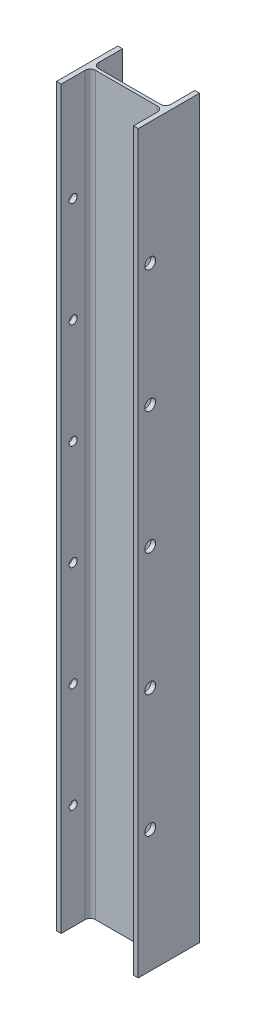
SolidWorks part; units mm, degrees
material "Plain Carbon Steel"
ref_plane "Front Plane" through (0, 0, 0) normal (0, 0, 1) x (1, 0, 0)
ref_plane "Top Plane" through (0, 0, 0) normal (0, 1, 0) x (1, 0, 0)
ref_plane "Right Plane" through (0, 0, 0) normal (1, 0, 0) x (0, 0, -1)
sketch3d "3DSketch1"
  line L1 (3.175, -457.2, -609.6) -> (3.175, -457.2, 0) construction
  line L2 (-3.175, -457.2, 0) -> (3.175, -457.2, 0) construction
  line L3 (53.975, -457.2, -38.1) -> (53.975, 457.2, -38.1)
  point P0 (53.975, -457.2, -38.1)
  point P6 (53.975, 457.2, -38.1)
  dimension "D1" = 50.8
  dimension "D2" = 38.1
other "Al i beam AL I BEAM 4X2.31(4)"
ref_plane "Plane1" through (53.975, -457.2, -38.1) normal (0, 1, 0) x (0, 0, -1)
sketch "Sketch11" plane through (53.975, -457.2, -38.1) normal (0, 1, 0) x (0, 0, -1)
  line L0 (-38.1, -50.8) -> (-38.1, -44.958)
  line L1 (-38.1, -44.958) -> (-8.255, -44.958)
  line L2 (-1.905, -38.608) -> (-1.905, 38.608)
  line L3 (-8.255, 44.958) -> (-38.1, 44.958)
  line L4 (-38.1, 44.958) -> (-38.1, 50.8)
  line L5 (-38.1, 50.8) -> (38.1, 50.8)
  line L6 (38.1, 50.8) -> (38.1, 44.958)
  line L7 (38.1, 44.958) -> (8.255, 44.958)
  line L8 (1.905, 38.608) -> (1.905, -38.608)
  line L9 (8.255, -44.958) -> (38.1, -44.958)
  line L10 (38.1, -44.958) -> (38.1, -50.8)
  line L11 (38.1, -50.8) -> (-38.1, -50.8)
  line L12 (1.905, 0) -> (-1.905, 0) construction
  arc A0 (-8.255, -44.958) -> (-1.905, -38.608) centre (-8.255, -38.608) ccw
  arc A1 (-1.905, 38.608) -> (-8.255, 44.958) centre (-8.255, 38.608) ccw
  arc A2 (8.255, 44.958) -> (1.905, 38.608) centre (8.255, 38.608) ccw
  arc A3 (1.905, -38.608) -> (8.255, -44.958) centre (8.255, -38.608) ccw
  point P20 (0, 50.8)
  point P23 (0.282, 0)
  point P25 (0, -50.8)
  point P26 (0, 0)
  dimension "Ri" = 6.35
  dimension "Tw" = 3.81
  dimension "Bf" = 76.2
  dimension "Depth" = 101.6
  dimension "Tf" = 5.842
sketch "Sketch12" plane through (3.175, 0, 0) normal (1, 0, 0) x (0, 0, -1)
  line L0 (0, -457.2) -> (29.845, -457.2)
  line L1 (0, -457.2) -> (76.2, -457.2) construction
  line L2 (29.845, 457.2) -> (29.845, -457.2) construction
  line L3 (14.9225, -326.5714) -> (14.9225, -457.2) construction
  point P8 (14.9225, -326.5714)
  point P10 (14.9225, -195.9429)
  point P12 (14.9225, -326.5714)
  point P13 (14.9225, -65.3143)
  point P14 (14.9225, 65.3143)
  point P15 (14.9225, 195.9429)
  point P16 (14.9225, 326.5714)
  dimension "D1" = 130.6286
  dimension "D3" = 261.2571
  dimension "D2" = 6
hole_wizard "3/8 Clearance Hole1" positions "Sketch12" profile "Sketch13" hole size "3/8" standard "ANSI Inch"
sketch "Sketch13" plane through (3.175, 326.5714, -14.9225) normal (0, 1, 0) x (0, 0, 1)
  line L0 (0, 0) -> (0, 101.6)
  line L1 (0, 101.6) -> (5.0419, 101.6)
  line L2 (5.0419, 101.6) -> (5.0419, 0)
  line L5 (5.0419, 0) -> (0, 0)
  line L11 (0, -6.35) -> (0, 107.95) construction
  dimension "Thru Hole Dia." = 10.0838
  dimension "Thru Hole Depth" = 101.6
sketch "Sketch14" plane through (98.933, 0, 0) normal (-1, 0, 0) x (0, 0, 1)
  line L0 (0, -457.2) -> (-29.845, -457.2)
  line L1 (-29.845, -457.2) -> (0, -457.2) construction
  point P4 (-14.9225, -304.8)
  point P6 (-14.9225, -457.2)
  point P8 (-14.9225, -152.4)
  point P9 (-14.9225, 0)
  point P10 (-14.9225, 152.4)
  point P11 (-14.9225, 304.8)
  dimension "D1" = 152.4
  dimension "D3" = 304.8
  dimension "D2" = 5
hole_wizard "1/2 Clearance Hole1" positions "Sketch14" profile "Sketch15" hole size "1/2" standard "ANSI Inch"
sketch "Sketch15" plane through (98.933, 304.8, -14.9225) normal (0, 1, 0) x (0, 0, 1)
  line L0 (0, 0) -> (0, 5.842)
  line L1 (0, 5.842) -> (6.7462, 5.842)
  line L2 (6.7462, 5.842) -> (6.7462, 0)
  line L5 (6.7462, 0) -> (0, 0)
  line L11 (0, -6.35) -> (0, 107.95) construction
  dimension "Thru Hole Dia." = 13.4925
  dimension "Thru Hole Depth" = 5.842
